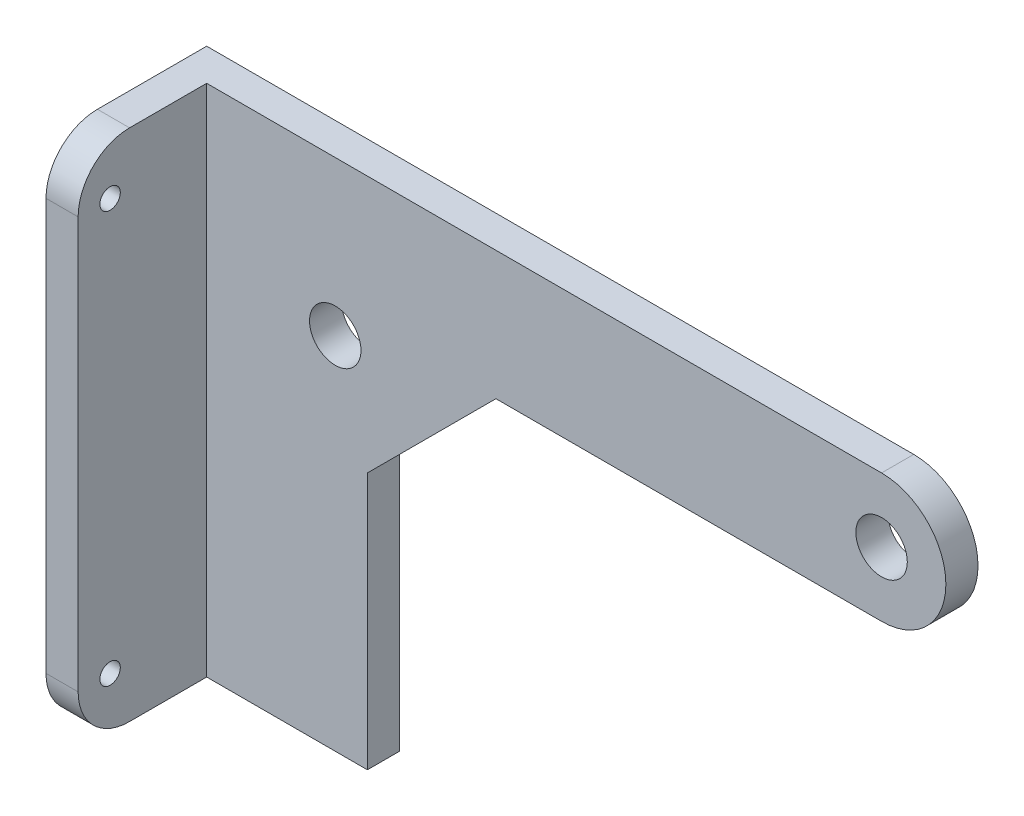
SolidWorks part; units mm, degrees
ref_plane "Front Plane" through (0, 0, 0) normal (0, 0, 1) x (1, 0, 0)
ref_plane "Top Plane" through (0, 0, 0) normal (0, 1, 0) x (1, 0, 0)
ref_plane "Right Plane" through (0, 0, 0) normal (1, 0, 0) x (0, 0, -1)
sketch "Sketch1" plane through (0, 0, 0) normal (0, 0, 1) x (1, 0, 0)
  line L0 (0, 110.5882) -> (0, -99.4118) construction
  line L1 (-117.0588, 0) -> (405, 0) construction
  line L3 (405, -50) -> (105, -50)
  line L4 (105, -50) -> (5, -150)
  line L5 (5, -150) -> (5, -350)
  line L6 (5, -350) -> (-145, -350)
  line L7 (-145, -350) -> (-145, 50)
  line L9 (-145, 50) -> (405, 50)
  arc A2 (405, 50) -> (405, -50) centre (405, 0) cw
  circle A3 centre (405, 0) radius 20
  circle A4 centre (-20, -70) radius 20
  dimension "D9" = 40
  dimension "D12" = 40
  dimension "D1" = 400
  dimension "D2" = 50
  dimension "D3" = 45
  dimension "D4" = 150
  dimension "D5" = 400
  dimension "D6" = 550
  dimension "D7" = 50
  dimension "D8" = 100
  dimension "D10" = 25
  dimension "D11" = 120
extrude "Boss-Extrude1" add sketch "Sketch1" along normal mid plane 25
sketch "Sketch2" plane through (0, 0, 12.5) normal (0, 0, 1) x (1, 0, 0)
  line L0 (405, 50) -> (-145, 50) construction
  line L1 (-145, -350) -> (-120, -350)
  line L2 (-145, -350) -> (-145, 50)
  line L3 (-145, 50) -> (-120, 50)
  line L4 (-120, -350) -> (-120, 50)
  dimension "D1" = 25
extrude "Boss-Extrude2" add sketch "Sketch2" along normal blind 100
sketch "Sketch3" plane through (-145, 0, 0) normal (-1, 0, 0) x (0, 0, 1)
  line L0 (112.5, 50) -> (112.5, -350) construction
  line L1 (112.5, -150) -> (-62.2155, -150) construction
  circle A0 centre (87.6484, 10) radius 7.94
  circle A1 centre (87.6484, -310) radius 7.94
  dimension "D3" = 15.88
  dimension "D4" = 15.88
  dimension "D1" = 320
  dimension "D2" = 160
extrude "Cut-Extrude1" cut sketch "Sketch3" against normal up to next
fillet "Fillet1" radius 40 2 edges at (-132.5, -350, 112.5) (-132.5, 50, 112.5)
